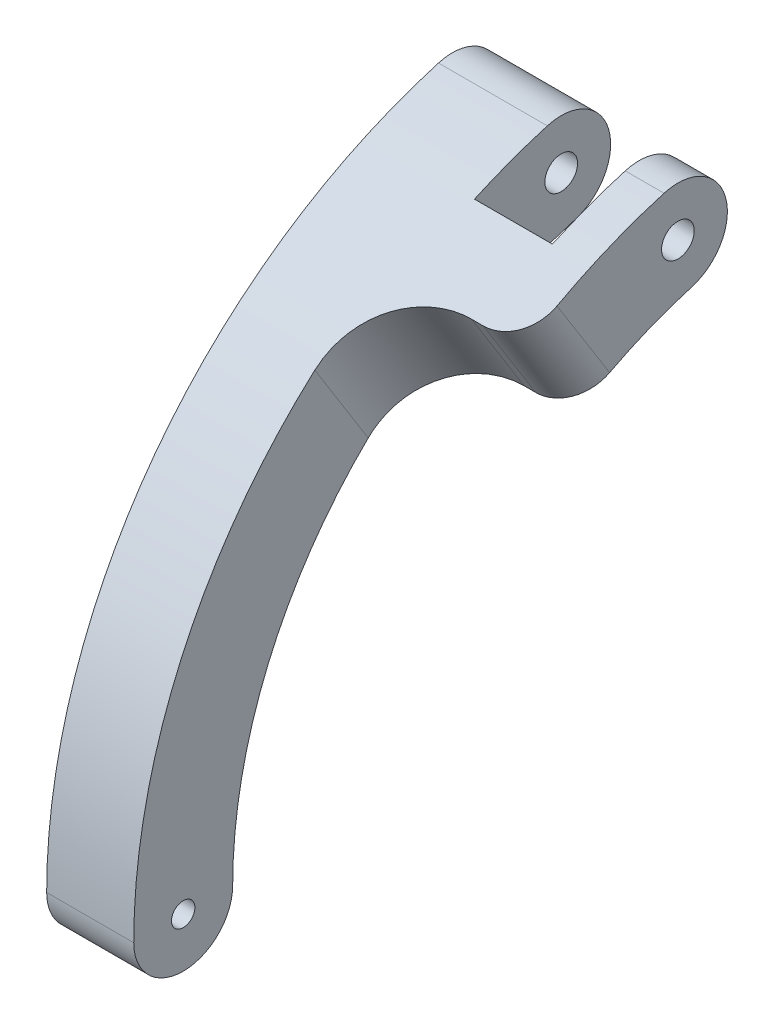
SolidWorks part; units mm, degrees
material "ABS"
ref_plane "Front Plane" through (0, 0, 0) normal (0, 0, 1) x (1, 0, 0)
ref_plane "Top Plane" through (0, 0, 0) normal (0, 1, 0) x (1, 0, 0)
ref_plane "Right Plane" through (0, 0, 0) normal (1, 0, 0) x (0, 0, -1)
sketch "Esquisse1" plane through (0, 0, 0) normal (1, 0, 0) x (0, 0, -1)
  arc A0 (-28.575, 0) -> (-8.001, 27.432) centre (0, 0) cw
  arc A1 (-34.925, 0) -> (-9.779, 33.528) centre (0, 0) cw
  arc A2 (-34.925, 0) -> (-28.575, 0) centre (-31.75, 0) ccw
  arc A3 (-8.001, 27.432) -> (-9.779, 33.528) centre (-8.89, 30.48) ccw
  circle A4 centre (-31.75, 0) radius 0.75
  circle A5 centre (-8.89, 30.48) radius 1.05
  dimension "D1" = 3.175
  dimension "D4" = 1.5
  dimension "D5" = 2.1
  dimension "D2" = 38.1
  dimension "D3" = 31.75
extrude "Boss.-Extru.1" add sketch "Esquisse1" along normal blind 5.588
sketch "Esquisse2" plane through (5.588, 0, 0) normal (1, 0, 0) x (0, 0, -1)
  line L0 (-15.4687, 24.026) -> (-18.8363, 29.41)
  arc A0 (-8.001, 27.432) -> (-28.575, 0) centre (0, 0) ccw construction
  arc A1 (-9.779, 33.528) -> (-34.925, 0) centre (0, 0) ccw construction
  arc A2 (-8.001, 27.432) -> (-9.779, 33.528) centre (-8.89, 30.48) ccw construction
  arc A3 (-8.001, 27.432) -> (-15.4687, 24.026) centre (0, 0) ccw
  arc A4 (-9.779, 33.528) -> (-18.8363, 29.41) centre (0, 0) ccw
  arc A5 (-8.001, 27.432) -> (-9.779, 33.528) centre (-8.89, 30.48) ccw
  dimension "D1" = 9
extrude "Boss.-Extru.2" add sketch "Esquisse2" along normal blind 8.89
ref_plane "Plan1" through (9.4878, 0, 0) normal (1, 0, 0) x (0, 0, -1)
sketch "Esquisse3" plane through (9.4878, 0, 0) normal (1, 0, 0) x (0, 0, -1)
  line L0 (-11.8578, 25.9985) -> (-14.455, 31.7932)
  arc A0 (-8.001, 27.432) -> (-15.4687, 24.026) centre (0, 0) ccw construction
  arc A1 (-8.001, 27.432) -> (-9.779, 33.528) centre (-8.89, 30.48) ccw construction
  arc A2 (-9.779, 33.528) -> (-18.8363, 29.41) centre (0, 0) ccw construction
  arc A3 (-8.001, 27.432) -> (-11.8578, 25.9985) centre (0, 0) ccw
  arc A4 (-8.001, 27.432) -> (-9.779, 33.528) centre (-8.89, 30.48) ccw
  arc A5 (-9.779, 33.528) -> (-14.455, 31.7932) centre (0, 0) ccw
extrude "Enlèv. mat.-Extru.1" cut sketch "Esquisse3" against normal mid plane 5
sketch "Esquisse4" plane through (0, 0, 0) normal (-1, 0, 0) x (0, 0, 1)
  circle A0 centre (8.89, 30.48) radius 1.05
  circle A1 centre (8.89, 30.48) radius 1.05 construction
extrude "Enlèv. mat.-Extru.2" cut sketch "Esquisse4" against normal through all
fillet "Congé1" radius 5.588 1 edges at (5.588, 26.718, 17.1525)
fillet "Congé2" radius 2.54 1 edges at (14.478, 26.718, 17.1525)
